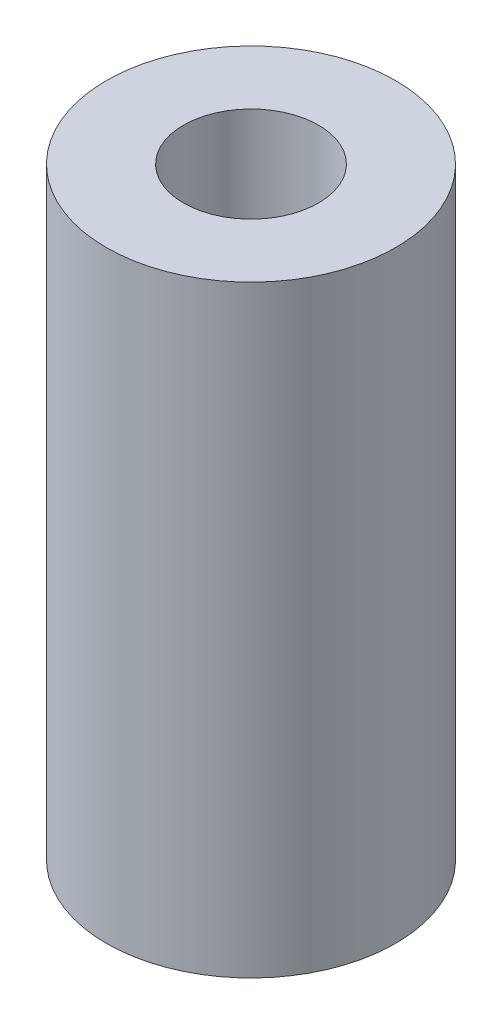
SolidWorks part; units mm, degrees
ref_plane "Front Plane" through (0, 0, 0) normal (0, 0, 1) x (1, 0, 0)
ref_plane "Top Plane" through (0, 0, 0) normal (0, 1, 0) x (1, 0, 0)
ref_plane "Right Plane" through (0, 0, 0) normal (1, 0, 0) x (0, 0, -1)
sketch "Sketch1" plane through (0, 0, 0) normal (0, 1, 0) x (1, 0, 0)
  line L0 (15.9252, 13.3522) -> (15.9252, -1.6478) construction
  line L1 (2.9252, 16.8522) -> (19.9252, 16.8522)
  line L2 (2.9252, 16.8522) -> (2.9252, -5.1478)
  line L3 (2.9252, -5.1478) -> (19.9252, -5.1478)
  line L4 (19.9252, 16.8522) -> (19.9252, -5.1478)
  line L5 (35.9252, 20.8522) -> (-114.0748, 20.8522) construction
  line L6 (35.9252, -61.1478) -> (35.9252, 20.8522) construction
  circle A0 centre (15.9252, 13.3522) radius 3
  point P7 (0, 0)
  point P8 (19.9252, 5.8522)
  point P9 (15.9252, 5.8522)
  dimension "D5" = 6
  dimension "D1" = 17
  dimension "D2" = 22
  dimension "D3" = 15
  dimension "D4" = 4
  dimension "D6" = 7.5
  dimension "D7" = 20
extrude "Boss-Extrude1" add sketch "Sketch1" along normal blind 12.5
sketch "Sketch2" plane through (0, 12.5, 0) normal (0, 1, 0) x (1, 0, 0)
  circle A0 centre (15.9252, 13.3522) radius 1.4
  dimension "D1" = 2.8
extrude "Cut-Extrude1" cut sketch "Sketch2" against normal blind 10
